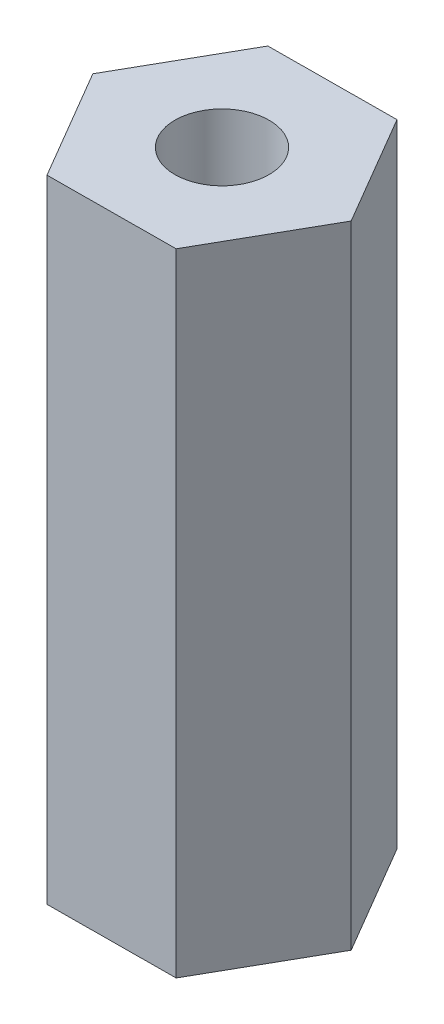
SolidWorks part; units mm, degrees
material "Stainless Steel (ferritic)"
ref_plane "Front Plane" through (0, 0, 0) normal (0, 0, 1) x (1, 0, 0)
ref_plane "Top Plane" through (0, 0, 0) normal (0, 1, 0) x (1, 0, 0)
ref_plane "Right Plane" through (0, 0, 0) normal (1, 0, 0) x (0, 0, -1)
sketch "Sketch2" plane through (0, 0, 0) normal (0, 1, 0) x (1, 0, 0)
  line L1 (2.9186, -4.9814) -> (5.7734, 0.0369)
  line L2 (5.7734, 0.0369) -> (2.8547, 5.0183)
  line L3 (2.8547, 5.0183) -> (-2.9186, 4.9814)
  line L4 (-2.9186, 4.9814) -> (-5.7734, -0.0369)
  line L5 (-5.7734, -0.0369) -> (-2.8547, -5.0183)
  line L6 (-2.8547, -5.0183) -> (2.9186, -4.9814)
  circle A0 centre (0, 0) radius 5 construction
  circle A1 centre (0, 0) radius 2.1209
  dimension "D3" = 4.2418
  dimension "D1" = 10
  dimension "D2" = 5.7734
extrude "Boss-Extrude1" add sketch "Sketch2" along normal blind 28.41
